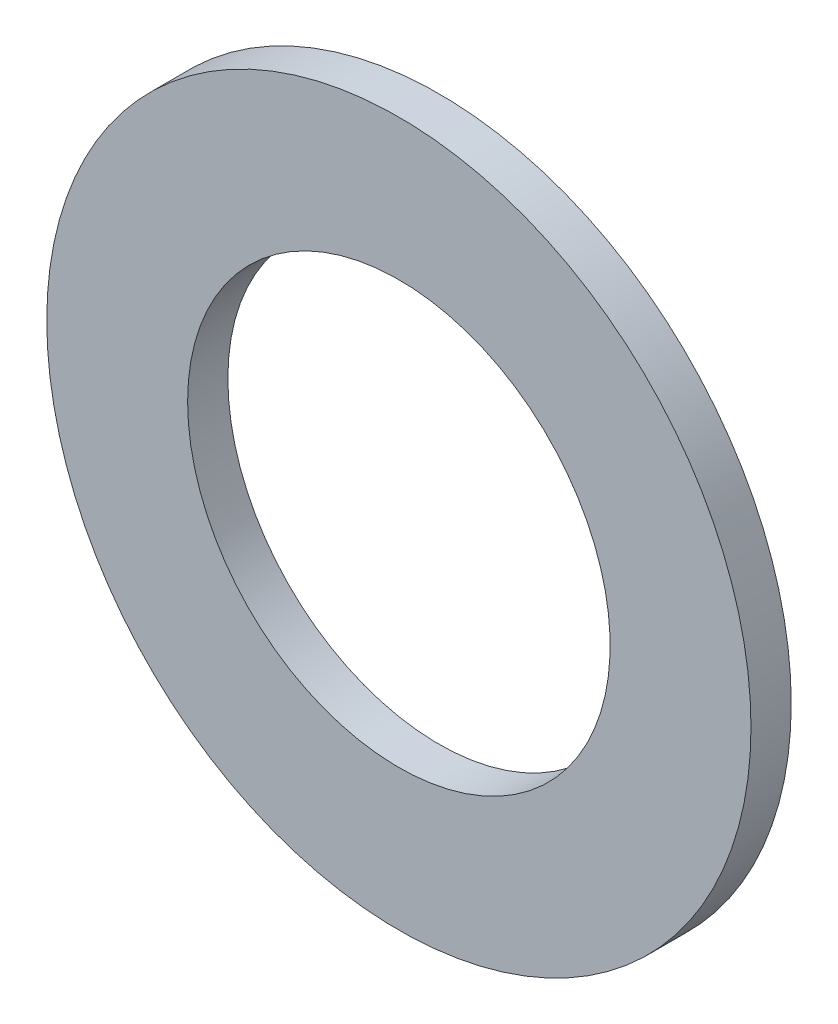
SolidWorks part; units mm, degrees
ref_plane "Plan de face" through (0, 0, 0) normal (0, 0, 1) x (1, 0, 0)
ref_plane "Plan de dessus" through (0, 0, 0) normal (0, 1, 0) x (1, 0, 0)
ref_plane "Plan de droite" through (0, 0, 0) normal (1, 0, 0) x (0, 0, -1)
sketch "Esquisse1" plane through (0, 0, 0) normal (0, 0, 1) x (1, 0, 0)
  circle A0 centre (0, 0) radius 10.5
  circle A1 centre (0, 0) radius 17.5
  dimension "D1" = 35
  dimension "D2" = 21
extrude "Boss.-Extru.1" add sketch "Esquisse1" along normal blind 2 contours A1
